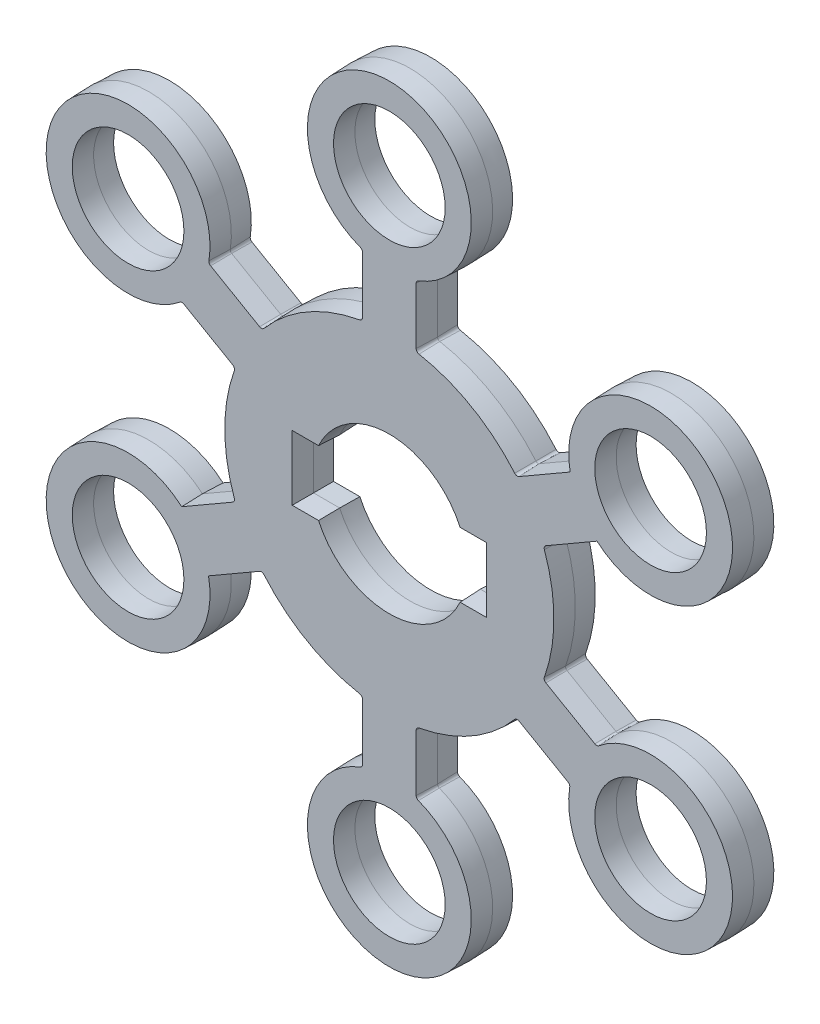
SolidWorks part; units mm, degrees
ref_plane "Front Plane" through (0, 0, 0) normal (0, 0, 1) x (1, 0, 0)
ref_plane "Top Plane" through (0, 0, 0) normal (0, 1, 0) x (1, 0, 0)
ref_plane "Right Plane" through (0, 0, 0) normal (1, 0, 0) x (0, 0, -1)
sketch "Sketch1" plane through (0, 0, 0) normal (0, 0, 1) x (1, 0, 0)
  line L0 (0, 0) -> (0, -44252.3868) construction
  line L1 (0, 0) -> (-44252.3868, 0) construction
  line L2 (-35, 11.5) -> (-25.5294, 11.5)
  line L3 (-35, -11.5) -> (-25.5294, -11.5)
  line L4 (35, -11.5) -> (25.5294, -11.5)
  line L5 (35, 11.5) -> (25.5294, 11.5)
  line L6 (-35, 11.5) -> (-35, -11.5)
  line L7 (35, 11.5) -> (35, -11.5)
  line L8 (-10, 80.5172) -> (-10, 60)
  line L9 (10, 80.5172) -> (10, 60)
  line L10 (75.3349, 31.9476) -> (56.9615, 21.3397)
  line L11 (65.3349, 49.2681) -> (46.9615, 38.6603)
  line L12 (64.73, -48.9189) -> (46.9615, -38.6603)
  line L13 (74.73, -31.5984) -> (56.9615, -21.3397)
  line L14 (-10, -80.5172) -> (-10, -60)
  line L15 (10, -80.5172) -> (10, -60)
  line L16 (-75.3349, -31.9476) -> (-56.9615, -21.3397)
  line L17 (-65.3349, -49.2681) -> (-46.9615, -38.6603)
  line L18 (-64.73, 48.9189) -> (-46.9615, 38.6603)
  line L19 (-74.73, 31.5984) -> (-56.9615, 21.3397)
  circle A0 centre (0, 0) radius 109.5 construction
  arc A1 (-10.8197, 59.0164) -> (-45.6999, 38.8783) centre (0, 0) ccw
  arc A2 (-25.5294, -11.5) -> (25.5294, -11.5) centre (0, 0) ccw
  arc A3 (25.5294, 11.5) -> (-25.5294, 11.5) centre (0, 0) ccw
  circle A4 centre (0, 109.5) radius 20
  arc A5 (10.6452, 81.4522) -> (-10.6452, 81.4522) centre (0, 109.5) ccw
  arc A6 (75.3349, 31.9476) -> (65.3349, 49.2681) centre (94.8298, 54.75) ccw
  circle A7 centre (94.8298, 54.75) radius 20
  arc A8 (65.2171, -49.9451) -> (75.8622, -31.5071) centre (94.8298, -54.75) ccw
  circle A9 centre (94.8298, -54.75) radius 20
  arc A10 (-10.6452, -81.4522) -> (10.6452, -81.4522) centre (0, -109.5) ccw
  circle A11 centre (0, -109.5) radius 20
  arc A12 (-75.3349, -31.9476) -> (-65.3349, -49.2681) centre (-94.8298, -54.75) ccw
  circle A13 centre (-94.8298, -54.75) radius 20
  arc A14 (-65.2171, 49.9451) -> (-75.8622, 31.5071) centre (-94.8298, 54.75) ccw
  circle A15 centre (-94.8298, 54.75) radius 20
  arc A16 (45.6999, 38.8783) -> (10.8197, 59.0164) centre (0, 0) ccw
  arc A17 (56.5195, -20.1381) -> (56.5195, 20.1381) centre (0, 0) ccw
  arc A18 (10.8197, -59.0164) -> (45.6999, -38.8783) centre (0, 0) ccw
  arc A19 (-45.6999, -38.8783) -> (-10.8197, -59.0164) centre (0, 0) ccw
  arc A20 (-56.5195, 20.1381) -> (-56.5195, -20.1381) centre (0, 0) ccw
  arc A21 (-56.9615, 21.3397) -> (-56.5195, 20.1381) centre (-57.4615, 20.4737) cw
  arc A22 (-56.9615, -21.3397) -> (-56.5195, -20.1381) centre (-57.4615, -20.4737) ccw
  arc A23 (-46.9615, -38.6603) -> (-45.6999, -38.8783) centre (-46.4615, -39.5263) cw
  arc A24 (-10, -80.5172) -> (-10.6452, -81.4522) centre (-11, -80.5172) cw
  arc A25 (-10, -60) -> (-10.8197, -59.0164) centre (-11, -60) ccw
  arc A26 (10, -80.5172) -> (10.6452, -81.4522) centre (11, -80.5172) ccw
  arc A27 (10, -60) -> (10.8197, -59.0164) centre (11, -60) cw
  arc A28 (46.9615, -38.6603) -> (45.6999, -38.8783) centre (46.4615, -39.5263) ccw
  arc A29 (64.73, -48.9189) -> (65.2171, -49.9451) centre (64.23, -49.7849) cw
  arc A30 (74.73, -31.5984) -> (75.8622, -31.5071) centre (75.23, -30.7323) ccw
  arc A31 (56.9615, -21.3397) -> (56.5195, -20.1381) centre (57.4615, -20.4737) cw
  arc A32 (56.9615, 21.3397) -> (56.5195, 20.1381) centre (57.4615, 20.4737) ccw
  arc A33 (-10, 60) -> (-10.8197, 59.0164) centre (-11, 60) cw
  arc A34 (10, 60) -> (10.8197, 59.0164) centre (11, 60) ccw
  arc A35 (10, 80.5172) -> (10.6452, 81.4522) centre (11, 80.5172) cw
  arc A36 (-10, 80.5172) -> (-10.6452, 81.4522) centre (-11, 80.5172) ccw
  arc A37 (-74.73, 31.5984) -> (-75.8622, 31.5071) centre (-75.23, 30.7323) ccw
  arc A38 (-46.9615, 38.6603) -> (-45.6999, 38.8783) centre (-46.4615, 39.5263) ccw
  arc A39 (-64.73, 48.9189) -> (-65.2171, 49.9451) centre (-64.23, 49.7849) cw
  arc A40 (46.9615, 38.6603) -> (45.6999, 38.8783) centre (46.4615, 39.5263) cw
  point P23 (0, 0)
  point P61 (0, 0)
  point P79 (-10, 59.1608)
  dimension "D1" = 35
  dimension "D3" = 56
  dimension "D4" = 120
  dimension "D5" = 219
  dimension "D6" = 40
  dimension "D7" = 60
  dimension "D11" = 1
  dimension "D2" = 23
  dimension "D8" = 60
  dimension "D9" = 20
  dimension "D10" = 6
extrude "Boss-Extrude1" add sketch "Sketch1" along normal mid plane 15 draft 2
